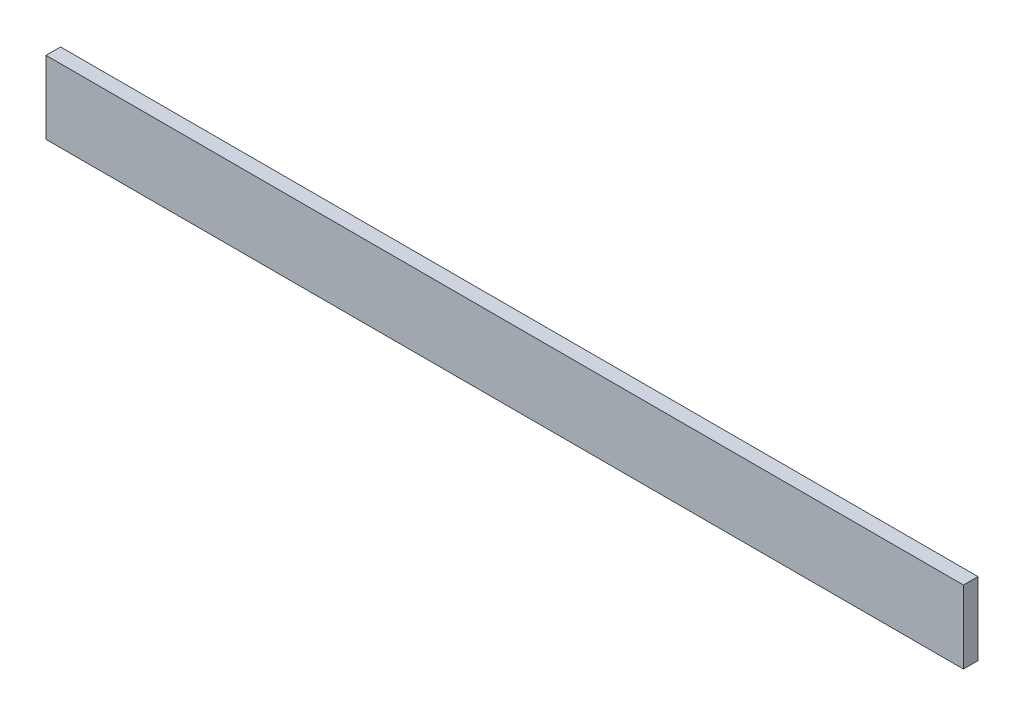
SolidWorks part; units mm, degrees
material "Akçaağaç"
ref_plane "Ön Düzlem" through (0, 0, 0) normal (0, 0, 1) x (1, 0, 0)
ref_plane "Üst Düzlem" through (0, 0, 0) normal (0, 1, 0) x (1, 0, 0)
ref_plane "Sağ Düzlem" through (0, 0, 0) normal (1, 0, 0) x (0, 0, -1)
sketch "Çizim1" plane through (0, 0, 0) normal (0, 0, 1) x (1, 0, 0)
  line L1 (315, -25) -> (-315, -25)
  line L2 (315, -25) -> (315, 25)
  line L3 (315, 25) -> (-315, 25)
  line L4 (-315, -25) -> (-315, 25)
  line L5 (315, -25) -> (-315, 25) construction
  line L6 (315, 25) -> (-315, -25) construction
  point P0 (0, 0)
  dimension "D1" = 630
  dimension "D2" = 50
extrude "Yükseklik-Ekstrüzyon1" add sketch "Çizim1" along normal blind 10
